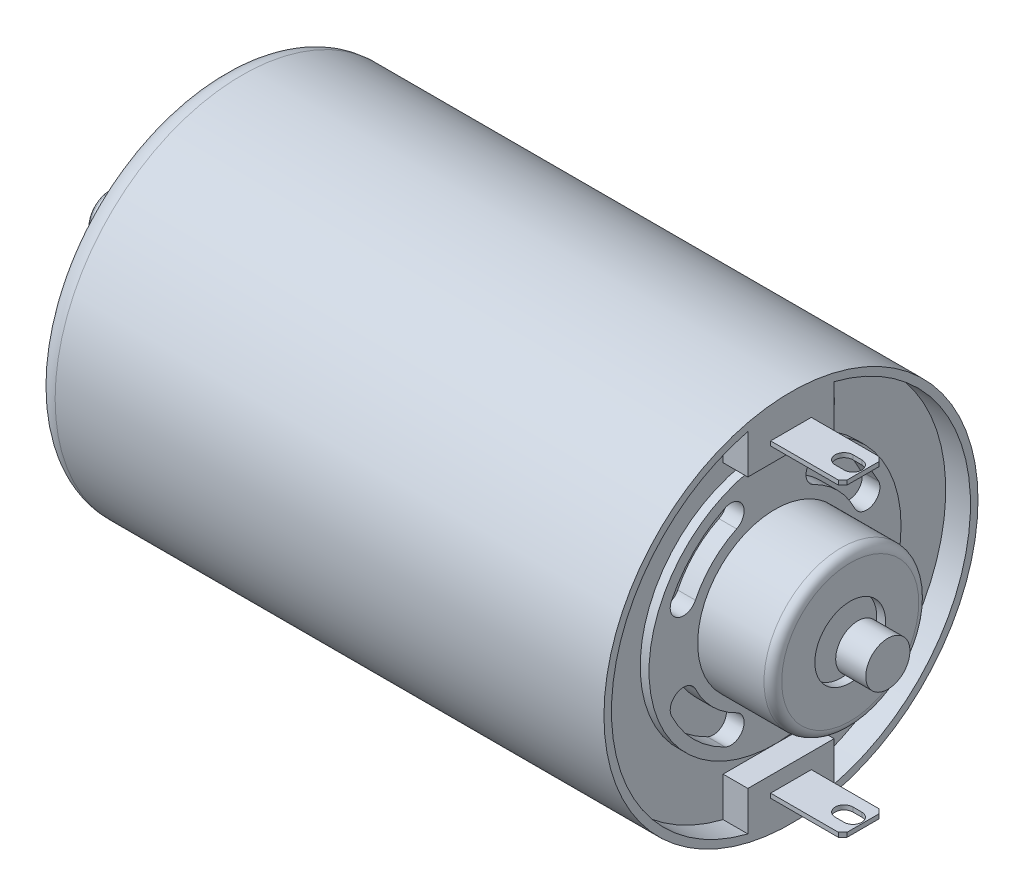
SolidWorks part; units mm, degrees
ref_plane "Спереди" through (0, 0, 0) normal (0, 0, 1) x (1, 0, 0)
ref_plane "Сверху" through (0, 0, 0) normal (0, 1, 0) x (1, 0, 0)
ref_plane "Справа" through (0, 0, 0) normal (1, 0, 0) x (0, 0, -1)
sketch "Эскиз1" plane through (0, 0, 0) normal (0, 0, 1) x (1, 0, 0)
  line L0 (6.7795, 21.15) -> (6.7795, 0)
  line L1 (6.7795, 0) -> (39.2445, 0)
  line L2 (39.2445, 0) -> (39.2445, 21.15)
  line L3 (39.2445, 21.15) -> (6.7795, 21.15)
  line L4 (6.7795, 0) -> (39.2445, 0) construction
  dimension "D1" = 21.15
revolve "Повернуть1" add sketch "Эскиз1" angle 360 about L4
sketch "Эскиз2" plane through (39.2445, 0, 0) normal (1, 0, 0) x (0, 0, -1)
  circle A0 centre (0, 0) radius 21.15
extrude "Бобышка-Вытянуть1" add sketch "Эскиз2" along normal blind 25
sketch "Эскиз3" plane through (64.2445, 0, 0) normal (1, 0, 0) x (0, 0, -1)
  line L0 (-2.3, 17) -> (-2.3, 17.5)
  line L1 (-2.3, 17.5) -> (2.3, 17.5)
  line L2 (2.3, 17.5) -> (2.3, 17)
  line L3 (2.3, 17) -> (-2.3, 17)
extrude "Бобышка-Вытянуть2" add sketch "Эскиз3" along normal blind 8.15
sketch "Эскиз4" plane through (0, 17.5, 0) normal (0, 1, 0) x (-1, 0, 0)
  line L0 (-71.25, -1) -> (-70.25, -1)
  line L1 (-70.25, 1) -> (-71.25, 1)
  arc A0 (-70.25, -1) -> (-70.25, 1) centre (-70.25, 0) ccw
  arc A1 (-71.25, 1) -> (-71.25, -1) centre (-71.25, 0) ccw
extrude "Вырез-Вытянуть1" cut sketch "Эскиз4" against normal through all
sketch "Эскиз5" plane through (64.2445, 0, 0) normal (1, 0, 0) x (0, 0, -1)
  line L0 (-2.3, -17.5) -> (-2.3, -17)
  line L1 (-2.3, -17) -> (2.3, -17)
  line L2 (2.3, -17) -> (2.3, -17.5)
  line L3 (2.3, -17.5) -> (-2.3, -17.5)
extrude "Бобышка-Вытянуть3" add sketch "Эскиз5" along normal blind 8.15
sketch "Эскиз6" plane through (0, -17.5, 0) normal (0, -1, 0) x (1, 0, 0)
  line L0 (71.25, 1) -> (70.25, 1)
  line L1 (70.25, -1) -> (71.25, -1)
  arc A0 (70.25, 1) -> (70.25, -1) centre (70.25, 0) ccw
  arc A1 (71.25, -1) -> (71.25, 1) centre (71.25, 0) ccw
extrude "Вырез-Вытянуть2" cut sketch "Эскиз6" against normal up to next
sketch "Эскиз7" plane through (64.2445, 0, 0) normal (1, 0, 0) x (0, 0, -1)
  line L0 (2.0689, 14.25) -> (2.0689, 15.25)
  line L1 (2.0689, 15.25) -> (-4.875, 15.25)
  line L2 (-4.875, 15.25) -> (-4.875, 19.7059)
  line L3 (-4.875, -19.7059) -> (-4.875, -15.25)
  line L4 (-4.875, -15.25) -> (4.875, -15.25)
  line L5 (4.875, -15.25) -> (4.875, -19.7059)
  line L6 (4.875, 19.7059) -> (4.875, 14.25)
  line L7 (4.875, 14.25) -> (2.0689, 14.25)
  arc A0 (-4.875, 19.7059) -> (-4.875, -19.7059) centre (0, 0) ccw
  arc A1 (4.875, -19.7059) -> (4.875, 19.7059) centre (0, 0) ccw
extrude "Вырез-Вытянуть3" cut sketch "Эскиз7" against normal blind 2.8
sketch "Эскиз8" plane through (61.4445, 0, 0) normal (1, 0, 0) x (0, 0, -1)
  circle A0 centre (0, 0) radius 14.25
extrude "Бобышка-Вытянуть4" add sketch "Эскиз8" along normal blind 1
sketch "Эскиз9" plane through (62.4445, 0, 0) normal (1, 0, 0) x (0, 0, -1)
  arc A0 (-5.6522, 11.707) -> (-11.707, 5.6522) centre (0, 0) ccw
  arc A1 (-11.707, 5.6522) -> (-9.0054, 4.3478) centre (-10.3562, 5) ccw
  arc A2 (-9.0054, 4.3478) -> (-4.3478, 9.0054) centre (0, 0) cw
  arc A3 (-4.3478, 9.0054) -> (-5.6522, 11.707) centre (-5, 10.3562) ccw
extrude "Вырез-Вытянуть4" cut sketch "Эскиз9" against normal blind 2
sketch "Эскиз10" plane through (62.4445, 0, 0) normal (1, 0, 0) x (0, 0, -1)
  arc A0 (11.707, 5.6522) -> (5.6522, 11.707) centre (0, 0) ccw
  arc A1 (5.6522, 11.707) -> (4.3478, 9.0054) centre (5, 10.3562) ccw
  arc A2 (4.3478, 9.0054) -> (9.0054, 4.3478) centre (0, 0) cw
  arc A3 (9.0054, 4.3478) -> (11.707, 5.6522) centre (10.3562, 5) ccw
extrude "Вырез-Вытянуть5" cut sketch "Эскиз10" against normal blind 2
sketch "Эскиз11" plane through (62.4445, 0, 0) normal (1, 0, 0) x (0, 0, -1)
  arc A0 (5.6522, -11.707) -> (11.707, -5.6522) centre (0, 0) ccw
  arc A1 (11.707, -5.6522) -> (9.0054, -4.3478) centre (10.3562, -5) ccw
  arc A2 (9.0054, -4.3478) -> (4.3478, -9.0054) centre (0, 0) cw
  arc A3 (4.3478, -9.0054) -> (5.6522, -11.707) centre (5, -10.3562) ccw
extrude "Вырез-Вытянуть6" cut sketch "Эскиз11" against normal blind 2
sketch "Эскиз12" plane through (62.4445, 0, 0) normal (1, 0, 0) x (0, 0, -1)
  arc A0 (-11.707, -5.6522) -> (-5.6522, -11.707) centre (0, 0) ccw
  arc A1 (-5.6522, -11.707) -> (-4.3478, -9.0054) centre (-5, -10.3562) ccw
  arc A2 (-4.3478, -9.0054) -> (-9.0054, -4.3478) centre (0, 0) cw
  arc A3 (-9.0054, -4.3478) -> (-11.707, -5.6522) centre (-10.3562, -5) ccw
extrude "Вырез-Вытянуть7" cut sketch "Эскиз12" against normal blind 2
sketch "Эскиз13" plane through (6.7795, 0, 0) normal (-1, 0, 0) x (0, 0, 1)
  circle A0 centre (0, 0) radius 21.15
extrude "Бобышка-Вытянуть5" add sketch "Эскиз13" along normal blind 7.1
sketch "Эскиз14" plane through (-0.3205, 0, 0) normal (-1, 0, 0) x (0, 0, 1)
  line L0 (6.7619, 14.5009) -> (4.7756, 10.2413)
  line L1 (10.2413, 4.7756) -> (14.5009, 6.7619)
  arc A0 (14.5009, 6.7619) -> (6.7619, 14.5009) centre (0, 0) ccw
  arc A1 (4.7756, 10.2413) -> (10.2413, 4.7756) centre (0, 0) cw
extrude "Вырез-Вытянуть8" cut sketch "Эскиз14" against normal blind 10
sketch "Эскиз15" plane through (-0.3205, 0, 0) normal (-1, 0, 0) x (0, 0, 1)
  line L0 (-6.7619, -14.5009) -> (-4.7756, -10.2413)
  line L1 (-10.2413, -4.7756) -> (-14.5009, -6.7619)
  arc A0 (-14.5009, -6.7619) -> (-6.7619, -14.5009) centre (0, 0) ccw
  arc A1 (-4.7756, -10.2413) -> (-10.2413, -4.7756) centre (0, 0) cw
extrude "Вырез-Вытянуть9" cut sketch "Эскиз15" against normal blind 10
sketch "Эскиз16" plane through (-0.3205, 0, 0) normal (-1, 0, 0) x (0, 0, 1)
  line L0 (-14.5009, 6.7619) -> (-10.2413, 4.7756)
  line L1 (-4.7756, 10.2413) -> (-6.7619, 14.5009)
  arc A0 (-6.7619, 14.5009) -> (-14.5009, 6.7619) centre (0, 0) ccw
  arc A1 (-10.2413, 4.7756) -> (-4.7756, 10.2413) centre (0, 0) cw
extrude "Вырез-Вытянуть10" cut sketch "Эскиз16" against normal blind 10
sketch "Эскиз17" plane through (-0.3205, 0, 0) normal (-1, 0, 0) x (0, 0, 1)
  line L0 (14.5009, -6.7619) -> (10.2413, -4.7756)
  line L1 (4.7756, -10.2413) -> (6.7619, -14.5009)
  arc A0 (6.7619, -14.5009) -> (14.5009, -6.7619) centre (0, 0) ccw
  arc A1 (10.2413, -4.7756) -> (4.7756, -10.2413) centre (0, 0) cw
extrude "Вырез-Вытянуть11" cut sketch "Эскиз17" against normal blind 10
sketch "Эскиз18" plane through (62.4445, 0, 0) normal (1, 0, 0) x (0, 0, -1)
  circle A0 centre (0, 0) radius 8.75
extrude "Бобышка-Вытянуть6" add sketch "Эскиз18" along normal blind 8.5
hole_wizard "Диаметр отверстия Ø8.0 (8)1" positions "Эскиз20" profile "Эскиз19" hole size "Ø8.0" standard "Ansi Metric"
sketch "Эскиз20" plane through (70.9445, 0, 0) normal (1, 0, 0) x (0, 0, -1)
  point P0 (0, 0)
sketch "Эскиз19" plane through (70.9445, 0, 0) normal (0, 1, 0) x (0, 0, -1)
  line L0 (0, 0) -> (0, 1)
  line L1 (0, 1) -> (4, 1)
  line L2 (4, 1) -> (4, 0)
  line L5 (4, 0) -> (0, 0)
  line L10 (0, 1) -> (-4, 1) construction
  line L11 (0, -6.35) -> (0, 107.95) construction
  dimension "Диаметр отверстия" = 8
  dimension "Глубина отверстия" = 1
  dimension "Угол заточки сверла" = 180
sketch "Эскиз21" plane through (-0.3205, 0, 0) normal (-1, 0, 0) x (0, 0, 1)
  circle A0 centre (0, 0) radius 8.9
extrude "Бобышка-Вытянуть7" add sketch "Эскиз21" along normal blind 5
hole_wizard "Отверстие с зазором M121" positions "Эскиз23" profile "Эскиз22" hole size "M12" standard "Ansi Metric"
sketch "Эскиз23" plane through (-5.3205, 0, 0) normal (-1, 0, 0) x (0, 0, 1)
  point P0 (0, 0)
sketch "Эскиз22" plane through (-5.3205, 0, 0) normal (0, 1, 0) x (0, 0, 1)
  line L0 (0, 0) -> (0, 1)
  line L1 (0, 1) -> (6.625, 1)
  line L2 (6.625, 1) -> (6.625, 0)
  line L5 (6.625, 0) -> (0, 0)
  line L10 (0, 1) -> (-6.625, 1) construction
  line L11 (0, -6.35) -> (0, 107.95) construction
  dimension "Диаметр отверстия" = 13.25
  dimension "Глубина отверстия" = 1
  dimension "Угол заточки сверла" = 180
ref_plane "Плоскость4" through (0, 0, 0) normal (0, 0, -1) x (-1, 0, 0)
sketch "Эскиз24" plane through (0, 0, 0) normal (0, 0, -1) x (-1, 0, 0)
  line L0 (4, 3.75) -> (4, 0)
  line L1 (4, 0) -> (12.8, 0)
  line L2 (12.8, 0) -> (12.8, 2.5)
  line L3 (12.8, 2.5) -> (5, 2.5)
  line L4 (5, 2.5) -> (5, 3.75)
  line L5 (5, 3.75) -> (4, 3.75)
  line L6 (4, 0) -> (12.8, 0) construction
revolve "Повернуть2" add sketch "Эскиз24" angle 360 about L6
sketch "Эскиз25" plane through (0, 0, 0) normal (0, 0, -1) x (-1, 0, 0)
  line L0 (-75.2, 2.5) -> (-75.2, 0)
  line L1 (-75.2, 0) -> (-71.8, 0)
  line L2 (-71.8, 0) -> (-71.8, 2.5)
  line L3 (-71.8, 2.5) -> (-75.2, 2.5)
  line L4 (-75.2, 0) -> (-71.8, 0) construction
revolve "Повернуть3" add sketch "Эскиз25" angle 360 about L4
hole_wizard "Диаметр отверстия Ø2.5 (2.5)1" positions "Эскиз27" profile "Эскиз26" hole size "Ø2.5" standard "Ansi Metric"
sketch "Эскиз27" plane through (61.4445, 0, 0) normal (1, 0, 0) x (0, 0, -1)
  point P0 (6.5, 15)
sketch "Эскиз26" plane through (61.4445, 15, -6.5) normal (0, 1, 0) x (0, 0, -1)
  line L0 (0, 0) -> (0, 0.1)
  line L1 (0, 0.1) -> (1.25, 0.1)
  line L2 (1.25, 0.1) -> (1.25, 0)
  line L5 (1.25, 0) -> (0, 0)
  line L10 (0, 0.1) -> (-1.25, 0.1) construction
  line L11 (0, -6.35) -> (0, 107.95) construction
  dimension "Диаметр отверстия" = 2.5
  dimension "Глубина отверстия" = 0.1
  dimension "Угол заточки сверла" = 180
hole_wizard "Диаметр отверстия Ø3.3 (3.3)1" positions "Эскиз29" profile "Эскиз28" hole size "Ø3.3" standard "Ansi Metric"
sketch "Эскиз29" plane through (-0.3205, 0, 0) normal (-1, 0, 0) x (0, 0, 1)
  point P0 (0, 14.5)
  point P1 (0, -14.5)
sketch "Эскиз28" plane through (-0.3205, 14.5, 0) normal (0, 1, 0) x (0, 0, 1)
  line L0 (0, 0) -> (0, 12.4914)
  line L1 (0, 12.4914) -> (1.65, 11.5)
  line L2 (1.65, 11.5) -> (1.65, 0)
  line L5 (1.65, 0) -> (0, 0)
  line L10 (0, 12.4914) -> (-1.65, 11.5) construction
  line L11 (0, -6.35) -> (0, 107.95) construction
  dimension "Диаметр отверстия" = 3.3
  dimension "Глубина отверстия" = 11.5
  dimension "Угол заточки сверла" = 118
chamfer "Фаска1" distance 0.5 angle 45 4 edges at (72.3945, 17.25, 2.3) (72.3945, -17.25, -2.3) (72.3945, 17.25, -2.3) (72.3945, -17.25, 2.3)
fillet "Скругление1" radius 0.25 1 edges at (-12.8, 0, 2.5)
fillet "Скругление2" radius 0.75 1 edges at (-5.3205, 0, 8.9)
fillet "Скругление3" radius 1 1 edges at (70.9445, 0, -8.75)
fillet "Скругление4" radius 2.5 1 edges at (-0.3205, 0, 21.15)
